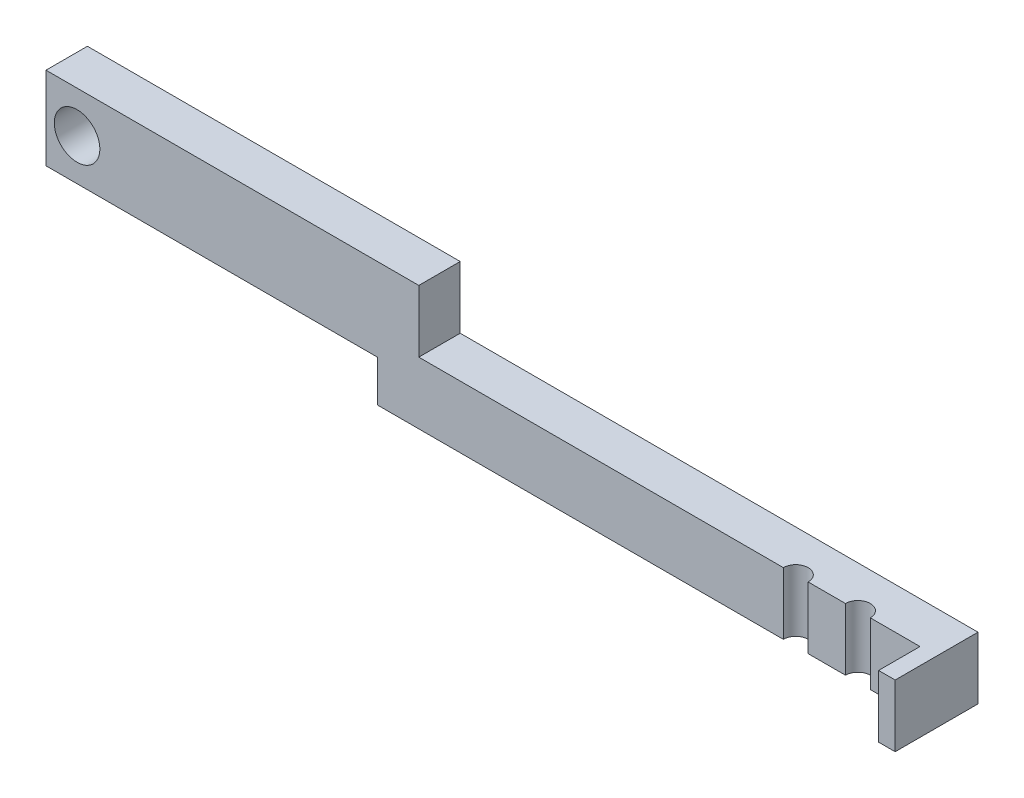
SolidWorks part; units mm, degrees
ref_plane "Alzado" through (0, 0, 0) normal (0, 0, 1) x (1, 0, 0)
ref_plane "Planta" through (0, 0, 0) normal (0, 1, 0) x (1, 0, 0)
ref_plane "Vista lateral" through (0, 0, 0) normal (1, 0, 0) x (0, 0, -1)
sketch "Croquis1" plane through (0, 0, 0) normal (0, 0, 1) x (1, 0, 0)
  line L0 (0, 0) -> (16, 0)
  line L1 (0, 0) -> (0, 4)
  line L2 (0, 4) -> (15, 4)
  line L4 (16, 0) -> (16, -2)
  line L5 (16, -2) -> (19, -2)
  line L6 (18, 1) -> (18, 4)
  line L7 (18, 4) -> (15, 4)
  line L8 (19, -2) -> (43, -2)
  line L9 (43, -2) -> (43, 1)
  line L10 (43, 1) -> (18, 1)
  dimension "D1" = 16
  dimension "D2" = 4
  dimension "D3" = 3
  dimension "D4" = 2
  dimension "D5" = 25
  dimension "D6" = 3
extrude "Saliente-Extruir1" add sketch "Croquis1" along normal blind 2
sketch "Croquis3" plane through (0, 0, 2) normal (0, 0, 1) x (1, 0, 0)
  line L0 (43, 1) -> (18, 1) construction
  line L1 (43, -2) -> (42.2, -2)
  line L2 (43, -2) -> (43, 1)
  line L3 (43, 1) -> (42.2, 1)
  line L4 (42.2, -2) -> (42.2, 1)
  dimension "D1" = 0.8
extrude "Saliente-Extruir2" add sketch "Croquis3" along normal blind 2
sketch "Croquis4" plane through (0, 1, 0) normal (0, 1, 0) x (1, 0, 0)
  line L0 (42.2, -2) -> (18, -2) construction
  circle A0 centre (39.2, -2) radius 0.6
  circle A1 centre (36.2, -2) radius 0.6
  dimension "D1" = 1.2
  dimension "D2" = 1.2
  dimension "D3" = 3
  dimension "D4" = 3
extrude "Cortar-Extruir1" cut sketch "Croquis4" against normal through all
sketch "Croquis5" plane through (0, 0, 0) normal (0, 0, -1) x (-1, 0, 0)
  line L0 (0, 4) -> (0, 0) construction
  line L1 (-18, 4) -> (0, 4) construction
  circle A0 centre (-1.5, 2) radius 1.1
  dimension "D1" = 2.2
  dimension "D2" = 1.5
  dimension "D3" = 2
extrude "Cortar-Extruir2" cut sketch "Croquis5" against normal through all
